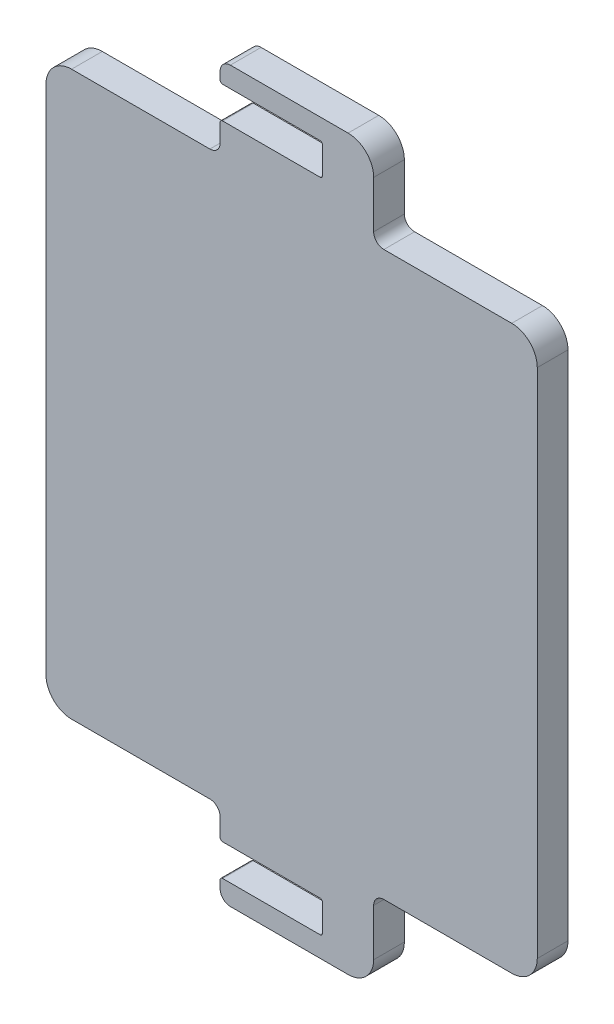
SolidWorks part; units mm, degrees
ref_plane "Alzado" through (0, 0, 0) normal (0, 0, 1) x (1, 0, 0)
ref_plane "Planta" through (0, 0, 0) normal (0, 1, 0) x (1, 0, 0)
ref_plane "Vista lateral" through (0, 0, 0) normal (1, 0, 0) x (0, 0, -1)
sketch "Croquis1" plane through (0, 0, 0) normal (0, 0, 1) x (1, 0, 0)
  line L0 (-9.0425, 0) -> (8.7011, 0) construction
  line L2 (-24, 25) -> (-24, -25)
  line L4 (24, 25) -> (24, -25)
  line L5 (-24, 27.5) -> (24, -27.5) construction
  line L6 (-24, -27.5) -> (24, 27.5) construction
  line L7 (-6.9873, 27.5) -> (-6.9873, 30.5)
  line L8 (-6.9873, 30.5) -> (3.0127, 30.5)
  line L9 (3.0127, 30.5) -> (3.0127, 33.6)
  line L10 (3.0127, 33.6) -> (-6.9873, 33.6)
  line L11 (-6.9873, 33.6) -> (-6.9873, 35.6)
  line L12 (-6.9873, 35.6) -> (5.5127, 35.6)
  line L13 (8.0127, 33.1) -> (8.0127, 27.5)
  line L14 (-21.5, 27.5) -> (-6.9873, 27.5)
  line L15 (8.0127, 27.5) -> (21.5, 27.5)
  line L16 (-6.9873, -33.6) -> (-6.9873, -35.6)
  line L17 (-6.9873, -27.5) -> (-6.9873, -30.5)
  line L18 (-6.9873, -30.5) -> (3.0127, -30.5)
  line L19 (3.0127, -30.5) -> (3.0127, -33.6)
  line L20 (3.0127, -33.6) -> (-6.9873, -33.6)
  line L21 (-6.9873, -35.6) -> (5.5127, -35.6)
  line L22 (8.0127, -33.1) -> (8.0127, -27.5)
  line L23 (8.0127, -27.5) -> (21.5, -27.5)
  line L24 (-6.9873, -27.5) -> (-21.5, -27.5)
  arc A0 (5.5127, 35.6) -> (8.0127, 33.1) centre (5.5127, 33.1) cw
  arc A1 (5.5127, -35.6) -> (8.0127, -33.1) centre (5.5127, -33.1) ccw
  arc A2 (-24, -25) -> (-21.5, -27.5) centre (-21.5, -25) ccw
  arc A3 (21.5, -27.5) -> (24, -25) centre (21.5, -25) ccw
  arc A4 (21.5, 27.5) -> (24, 25) centre (21.5, 25) cw
  arc A5 (-21.5, 27.5) -> (-24, 25) centre (-21.5, 25) ccw
  point P0 (0, 0)
  point P19 (8.0127, 35.6)
  dimension "D9" = 2.5
  dimension "D10" = 2.5
  dimension "D1" = 55
  dimension "D2" = 48
  dimension "D3" = 10
  dimension "D4" = 10
  dimension "D5" = 3.1
  dimension "D6" = 2
  dimension "D7" = 3
  dimension "D8" = 15
  dimension "D11" = 8.1
extrude "Saliente-Extruir2" add sketch "Croquis1" along normal blind 3
fillet "Redondeo1" radius 1 6 edges at (-6.9873, 27.5, 1.5) (-6.9873, 35.6, 1.5) (8.0127, 27.5, 1.5) (8.0127, -27.5, 1.5) (-6.9873, -27.5, 1.5) (-6.9873, -35.6, 1.5)
fillet "Redondeo2" radius 0.25 8 edges at (3.0127, 30.5, 1.5) (-6.9873, 30.5, 1.5) (3.0127, 33.6, 1.5) (-6.9873, 33.6, 1.5) (3.0127, -30.5, 1.5) (3.0127, -33.6, 1.5) (-6.9873, -33.6, 1.5) (-6.9873, -30.5, 1.5)
